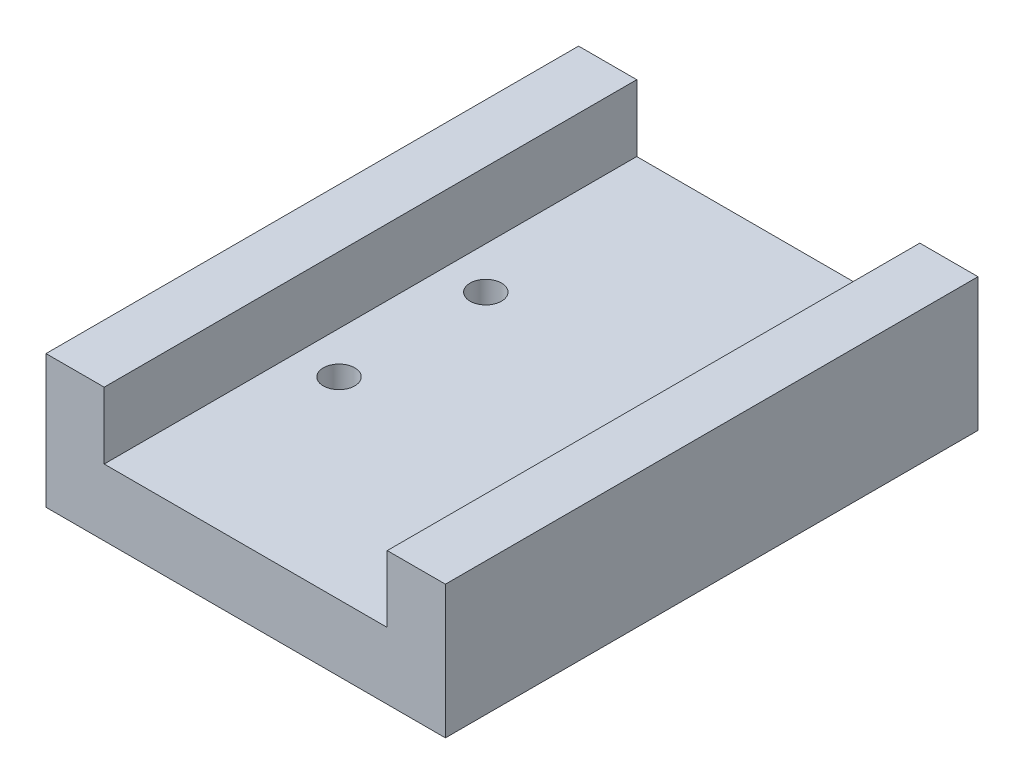
SolidWorks part; units mm, degrees
ref_plane "Front Plane" through (0, 0, 0) normal (0, 0, 1) x (1, 0, 0)
ref_plane "Top Plane" through (0, 0, 0) normal (0, 1, 0) x (1, 0, 0)
ref_plane "Right Plane" through (0, 0, 0) normal (1, 0, 0) x (0, 0, -1)
sketch "Sketch1" plane through (0, 0, 0) normal (0, 0, 1) x (1, 0, 0)
  line L1 (-19.05, 6.35) -> (19.05, 6.35)
  line L2 (-19.05, 6.35) -> (-19.05, 0)
  line L3 (-19.05, 0) -> (19.05, 0)
  line L4 (19.05, 6.35) -> (19.05, 0)
  line L5 (19.05, 0) -> (13.5, 0)
  line L6 (19.05, 0) -> (19.05, 12.7)
  line L7 (19.05, 12.7) -> (13.5, 12.7)
  line L8 (13.5, 0) -> (13.5, 12.7)
  line L9 (-19.05, 0) -> (-13.5, 0)
  line L10 (-19.05, 0) -> (-19.05, 12.7)
  line L11 (-19.05, 12.7) -> (-13.5, 12.7)
  line L12 (-13.5, 0) -> (-13.5, 12.7)
  point P10 (0, 0)
  point P11 (8.8676, 12.7)
  dimension "D1" = 6.35
  dimension "D2" = 12.7
  dimension "D3" = 27
  dimension "D4" = 38.1
extrude "Boss-Extrude1" add sketch "Sketch1" along normal blind 50.8 contours L1 L12 L11 L10 | L3 L12 L1 L2 | L12 L3 L8 L1 | L8 L1 L6 L7 | L8 L3 L4 L1
sketch "Sketch2" plane through (0, 0, 0) normal (0, 1, 0) x (1, 0, 0)
  line L0 (-19.05, -25.4) -> (19.05, -25.4) construction
  line L1 (-19.05, -50.8) -> (-19.05, 0) construction
  line L2 (19.05, -50.8) -> (19.05, 0) construction
  line L3 (-13.5, -50.8) -> (-13.5, 0) construction
  line L4 (-8.1252, -16.0188) -> (-10.8748, -16.0188)
  line L5 (-10.8748, -16.0188) -> (-12.2496, -18.4)
  line L6 (-12.2496, -18.4) -> (-10.8748, -20.7812)
  line L7 (-10.8748, -20.7812) -> (-8.1252, -20.7812)
  line L8 (-8.1252, -20.7812) -> (-6.7504, -18.4)
  line L9 (-6.7504, -18.4) -> (-8.1252, -16.0188)
  line L10 (-6.7504, -32.4) -> (-8.1252, -34.7812)
  line L11 (-8.1252, -30.0187) -> (-6.7504, -32.4)
  line L12 (-10.8748, -30.0187) -> (-8.1252, -30.0187)
  line L13 (-12.2496, -32.4) -> (-10.8748, -30.0187)
  line L14 (-10.8748, -34.7812) -> (-12.2496, -32.4)
  line L15 (-8.1252, -34.7812) -> (-10.8748, -34.7812)
  circle A0 centre (-9.5, -18.4) radius 1.5
  circle A1 centre (-9.5, -18.4) radius 2.3812 construction
  circle A2 centre (-9.5, -32.4) radius 2.3812 construction
  circle A3 centre (-9.5, -32.4) radius 1.5
  point P8 (-6.7297, -17.8886)
  point P16 (-7.5459, -18.4)
  dimension "D1" = 3
  dimension "D3" = 4.7625
  dimension "D2" = 14
  dimension "D4" = 4
extrude "Cut-Extrude1" cut sketch "Sketch2" along normal through all contours A3 | A0
